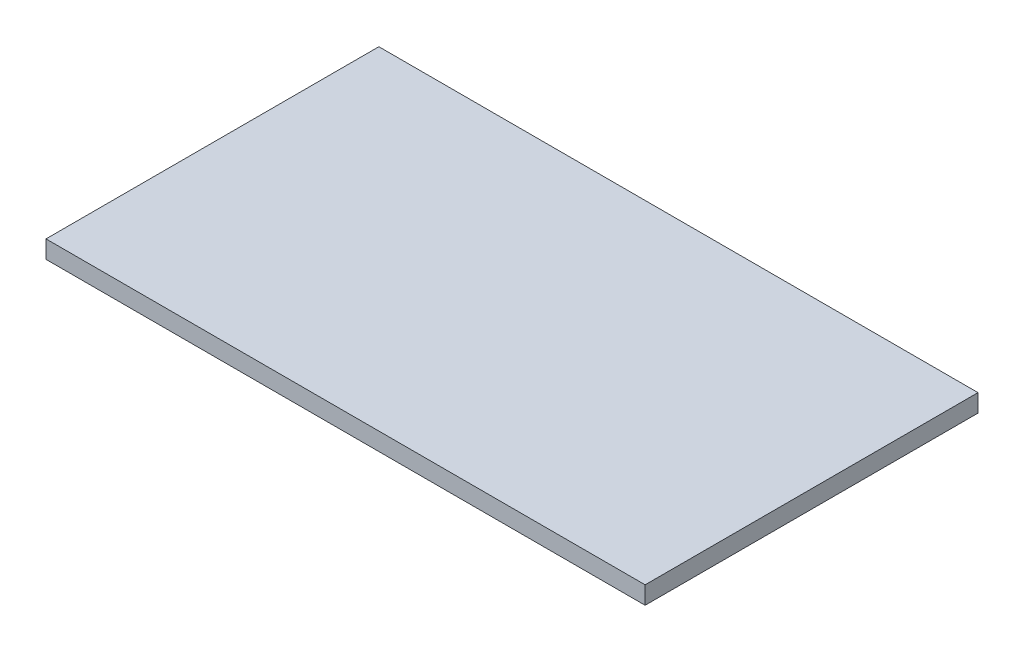
SolidWorks part; units mm, degrees
material "Клен"
ref_plane "Спереди (XY)" through (0, 0, 0) normal (0, 0, 1) x (1, 0, 0)
ref_plane "Сверху (XZ)" through (0, 0, 0) normal (0, 1, 0) x (1, 0, 0)
ref_plane "Справа (ZY)" through (0, 0, 0) normal (1, 0, 0) x (0, 0, -1)
sketch "Эскиз1" plane through (0, 0, 0) normal (0, 1, 0) x (1, 0, 0)
  line L1 (135, 75) -> (-135, 75)
  line L2 (135, 75) -> (135, -75)
  line L3 (135, -75) -> (-135, -75)
  line L4 (-135, 75) -> (-135, -75)
  line L5 (135, 75) -> (-135, -75) construction
  line L6 (135, -75) -> (-135, 75) construction
  point P0 (0, 0)
  dimension "D1" = 150
  dimension "D2" = 270
extrude "Бобышка-Вытянуть1" add sketch "Эскиз1" along normal blind 8
